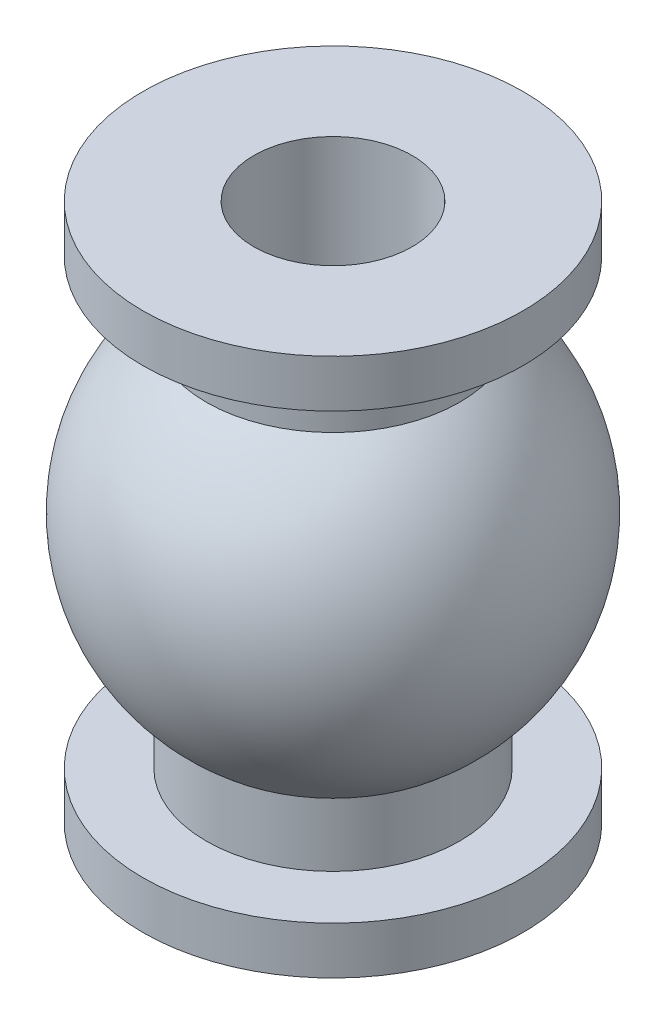
SolidWorks part; units mm, degrees
ref_plane "Front Plane" through (0, 0, 0) normal (0, 0, 1) x (1, 0, 0)
ref_plane "Top Plane" through (0, 0, 0) normal (0, 1, 0) x (1, 0, 0)
ref_plane "Right Plane" through (0, 0, 0) normal (1, 0, 0) x (0, 0, -1)
sketch "Sketch1" plane through (0, 0, 0) normal (0, 0, 1) x (1, 0, 0)
  line L0 (0, 16.1142) -> (0, -14.1472) construction
  line L1 (-9.6837, 5) -> (0, 5) construction
  line L2 (-10.4402, -5) -> (0, -5) construction
  line L3 (-12.9368, 7) -> (-4, 7) construction
  line L4 (-6, 7) -> (-4, 7)
  line L6 (0, 8.5) -> (-6, 8.5)
  line L7 (-6, 8.5) -> (-6, 7)
  line L8 (-4, 7) -> (-4, 5)
  line L9 (6.4031, 0) -> (16.2655, 0) construction
  line L10 (-17.5138, 0) -> (0, 0) construction
  line L11 (6, 7) -> (15.3955, 7) construction
  line L12 (4, -5) -> (14.6011, -5) construction
  line L16 (0, -8.5) -> (-6, -8.5)
  line L17 (-6, -8.5) -> (-6, -7)
  line L18 (-6, -7) -> (-4, -7)
  line L19 (-4, -7) -> (-4, -5)
  line L20 (-7, 10.5881) -> (-7, -8.9601) construction
  line L21 (4, 5) -> (15.9629, 5) construction
  line L22 (0, -8.5) -> (0, 8.5)
  arc A0 (-4, 5) -> (-4, -5) centre (0, 0) ccw
  dimension "D1" = 7
  dimension "D4" = 2
  dimension "D6" = 6
  dimension "D7" = 1.5
  dimension "D8" = 4
revolve "Revolve1" add sketch "Sketch1" angle 360 about L0
sketch "Sketch2" plane through (0, 8.5, 0) normal (0, 1, 0) x (1, 0, 0)
  circle A0 centre (0, 0) radius 2.5
  dimension "D1" = 5
extrude "Cut-Extrude1" cut sketch "Sketch2" against normal through all
